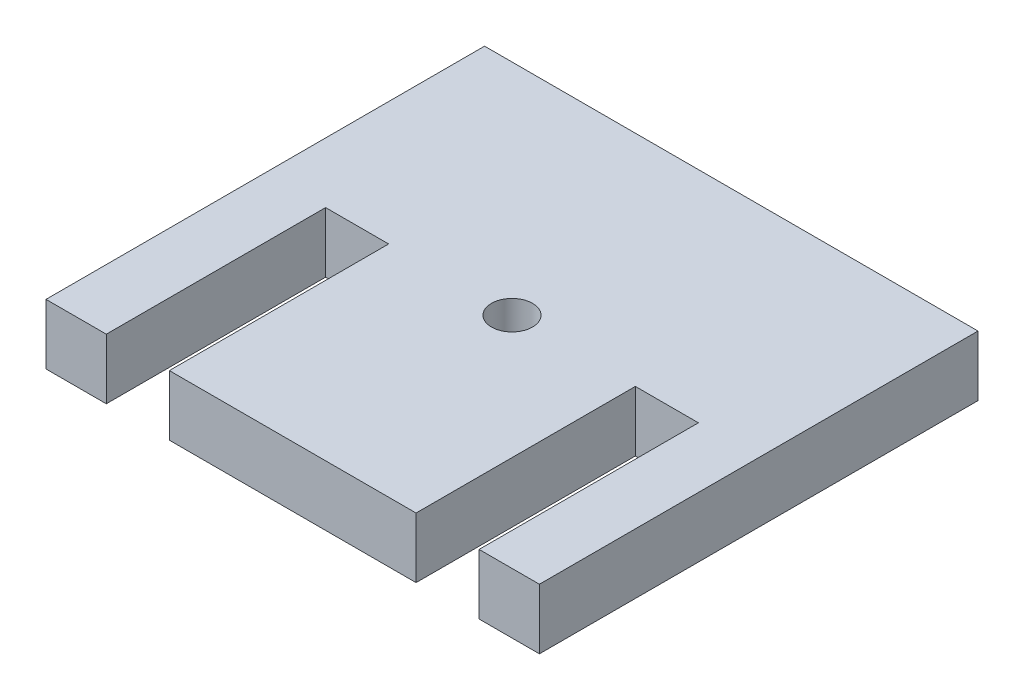
SolidWorks part; units mm, degrees
material "cardboard"
ref_plane "Front Plane" through (0, 0, 0) normal (0, 0, 1) x (1, 0, 0)
ref_plane "Top Plane" through (0, 0, 0) normal (0, 1, 0) x (1, 0, 0)
ref_plane "Right Plane" through (0, 0, 0) normal (1, 0, 0) x (0, 0, -1)
sketch "Sketch1" plane through (0, 0, 0) normal (0, 1, 0) x (1, 0, 0)
  line L0 (-9.2929, 15.5977) -> (44.5071, 15.5977)
  line L1 (-65.4929, 15.5977) -> (-11.6929, 15.5977)
  line L2 (-65.4929, 15.5977) -> (-65.4929, -0.2023)
  line L3 (-65.4929, -0.2023) -> (44.5071, -0.2023)
  line L4 (44.5071, 15.5977) -> (44.5071, -0.2023)
  line L5 (-11.6929, 15.5977) -> (-11.6929, 7.6977)
  line L6 (-9.2929, 15.5977) -> (-9.2929, 7.6977)
  line L7 (-11.6929, 7.6977) -> (-9.2929, 7.6977)
  line L8 (-9.2929, -0.4023) -> (44.5071, -0.4023)
  line L9 (-65.4929, -0.4023) -> (-11.6929, -0.4023)
  line L10 (-65.4929, -0.4023) -> (-65.4929, -16.2023)
  line L11 (-65.4929, -16.2023) -> (44.5071, -16.2023)
  line L12 (44.5071, -0.4023) -> (44.5071, -16.2023)
  line L13 (-11.6929, -0.4023) -> (-11.6929, -8.3023)
  line L14 (-9.2929, -0.4023) -> (-9.2929, -8.3023)
  line L15 (-11.6929, -8.3023) -> (-9.2929, -8.3023)
  line L16 (-65.4929, -16.4023) -> (-11.6929, -16.4023)
  line L17 (49.6929, 7.5977) -> (49.6929, -0.4023)
  line L18 (47.4929, 15.5977) -> (65.4929, 15.5977)
  line L19 (47.4929, -0.4023) -> (49.6929, -0.4023)
  line L20 (51.9929, 7.5977) -> (51.9929, -0.4023)
  line L21 (60.9929, 7.5977) -> (60.9929, -0.4023)
  line L22 (49.6929, 7.5977) -> (51.9929, 7.5977)
  line L23 (60.9929, 7.5977) -> (63.2929, 7.5977)
  line L24 (51.9929, -0.4023) -> (60.9929, -0.4023)
  line L25 (63.2929, 7.5977) -> (63.2929, -0.4023)
  line L26 (63.2929, -0.4023) -> (65.4929, -0.4023)
  line L27 (47.4929, 15.5977) -> (47.4929, -0.4023)
  line L28 (65.4929, 15.5977) -> (65.4929, -0.4023)
  circle A0 centre (56.4929, 7.5977) radius 0.75
extrude "Boss-Extrude1" add sketch "Sketch1" along normal blind 2.2 contours L28 L18 L27 L19 L17 L22 L20 L24 L21 L23 L25 L26 A0
